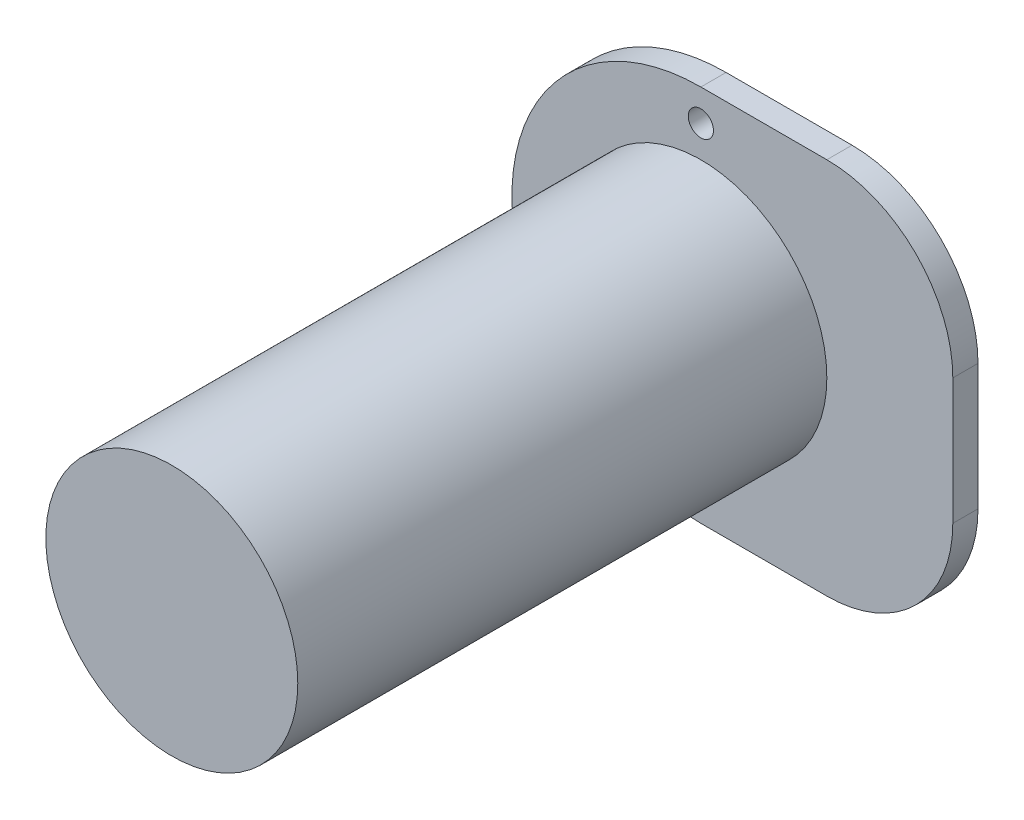
SolidWorks part; units mm, degrees
ref_plane "Front Plane" through (0, 0, 0) normal (0, 0, 1) x (1, 0, 0)
ref_plane "Top Plane" through (0, 0, 0) normal (0, 1, 0) x (1, 0, 0)
ref_plane "Right Plane" through (0, 0, 0) normal (1, 0, 0) x (0, 0, -1)
sketch "Sketch1" plane through (0, 0, 0) normal (0, 0, 1) x (1, 0, 0)
  circle A0 centre (0, 0) radius 50
  dimension "D1" = 100
extrude "Boss-Extrude1" add sketch "Sketch1" along normal mid plane 210
sketch "Sketch2" plane through (0, 0, -105) normal (0, 0, -1) x (-1, 0, 0)
  line L1 (0, -75) -> (-100, -75)
  line L3 (0, 75) -> (-100, 75)
  line L4 (-100, -75) -> (-100, 75)
  arc A0 (0, -75) -> (0, 75) centre (0, 0) ccw
  point P7 (0, 75.4915)
  dimension "D1" = 150
  dimension "D2" = 100
extrude "Boss-Extrude2" add sketch "Sketch2" along normal blind 10
sketch "Sketch3" plane through (0, 0, -115) normal (0, 0, -1) x (-1, 0, 0)
  circle A0 centre (0, 0) radius 62.5 construction
  circle A1 centre (0, 62.5) radius 5
  circle A2 centre (0, -62.5) radius 5
  circle A3 centre (62.5, 0) radius 5
  dimension "D1" = 10
  dimension "D2" = 125
extrude "Cut-Extrude1" cut sketch "Sketch3" against normal blind 10
fillet "Fillet1" radius 50 2 edges at (100, 75, -110) (100, -75, -110)
